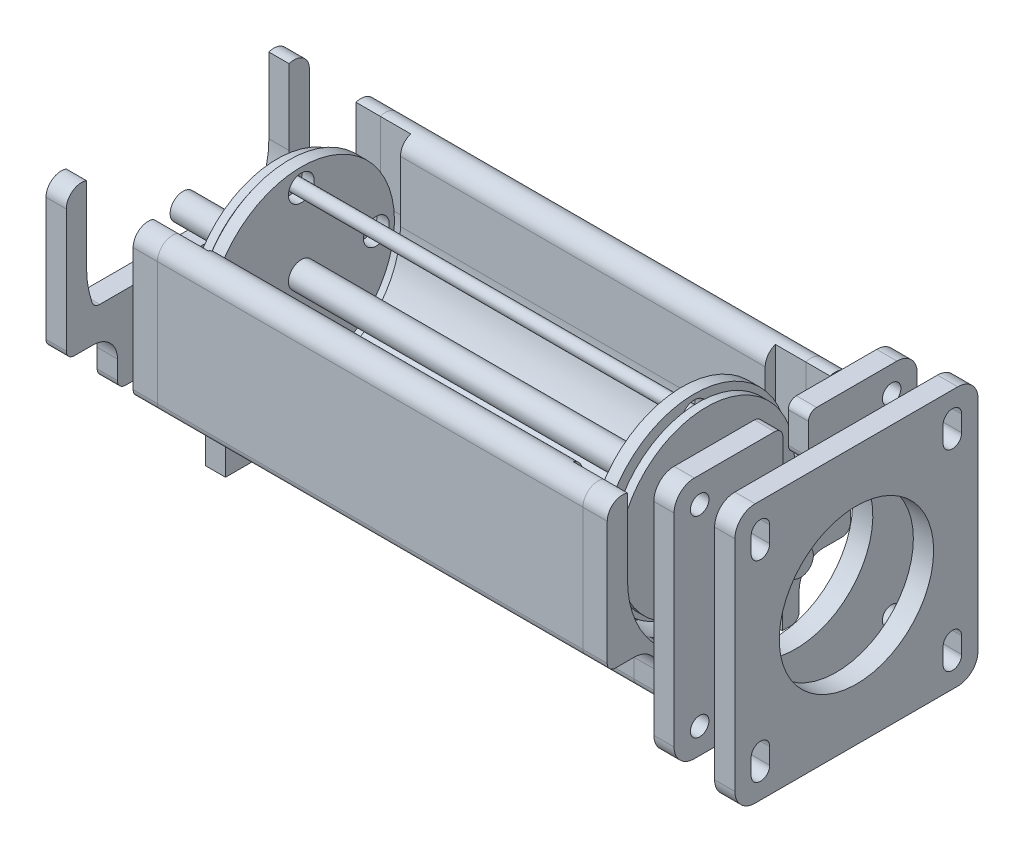
SolidWorks part; units mm, degrees
ref_plane "Front Plane" through (0, 0, 0) normal (0, 0, 1) x (1, 0, 0)
ref_plane "Top Plane" through (0, 0, 0) normal (0, 1, 0) x (1, 0, 0)
ref_plane "Right Plane" through (0, 0, 0) normal (1, 0, 0) x (0, 0, -1)
ref_plane "Plane1" through (-50, 0, 0) normal (1, 0, 0) x (0, 0, -1)
sketch "Sketch2" plane through (-50, 0, 0) normal (1, 0, 0) x (0, 0, -1)
  line L0 (0, 0) -> (0, 1.0694) construction
  circle A0 centre (0, 0) radius 3.175
  circle A1 centre (0, 18.5125) radius 1.5875 construction
  circle A2 centre (0, 18.5125) radius 3.175
  circle A3 centre (0, 0) radius 23
  circle A4 centre (-18.5125, 0) radius 1.5875 construction
  circle A5 centre (-18.5125, 0) radius 3.175
  circle A6 centre (0, -18.5125) radius 1.5875 construction
  circle A7 centre (0, -18.5125) radius 3.175
  circle A8 centre (18.5125, 0) radius 1.5875 construction
  circle A9 centre (18.5125, 0) radius 3.175
  dimension "D1" = 6.35
  dimension "D2" = 3.175
  dimension "D3" = 6.35
  dimension "D4" = 46
extrude "Boss-Extrude2" add sketch "Sketch2" along normal blind 3 separate body
ref_plane "Plane2" through (45, 0, 0) normal (1, 0, 0) x (0, 0, -1)
sketch "Sketch3" plane through (45, 0, 0) normal (1, 0, 0) x (0, 0, -1)
  line L0 (-22.4812, 0) -> (-22.4812, 15)
  line L1 (22.4812, 0) -> (22.4812, 15)
  line L2 (-23.371, -17.371) -> (-30, -17.371)
  line L3 (-30, 15) -> (-30, -17.371)
  line L4 (-17.371, -30) -> (17.371, -30)
  line L5 (-17.371, -23.371) -> (-17.371, -30)
  line L6 (17.371, -23.371) -> (17.371, -30)
  line L7 (23.371, -17.371) -> (30, -17.371)
  line L12 (30, -17.371) -> (30, 15)
  arc A0 (-22.4812, 0) -> (22.4812, 0) centre (0, 0) ccw
  arc A1 (-23.371, -17.371) -> (-17.371, -23.371) centre (-23.371, -23.371) cw
  arc A2 (17.371, -23.371) -> (23.371, -17.371) centre (23.371, -23.371) cw
  arc A3 (-30, 15) -> (-22.4812, 15) centre (-26.2406, 15) cw
  arc A4 (30, 15) -> (22.4812, 15) centre (26.2406, 15) ccw
  dimension "D1" = 6
  dimension "D2" = 6
extrude "Boss-Extrude3" add sketch "Sketch3" against normal blind 90 separate body
fillet "Fillet1" radius 2 4 edges at (0, -30, -17.371) (0, -30, 17.371) (0, -17.371, 30) (0, -17.371, -30)
ref_plane "Plane9" through (-51, 0, 0) normal (1, 0, 0) x (0, 0, -1)
sketch "Sketch16" plane through (-51, 0, 0) normal (1, 0, 0) x (0, 0, -1)
  circle A0 centre (0, 0) radius 21.6875
  circle A1 centre (0, 0) radius 3.175
  dimension "D1" = 6.35
extrude "Boss-Extrude7" add sketch "Sketch16" against normal blind 2 separate body
sketch "Sketch21" plane through (0, 0, 0) normal (1, 0, 0) x (0, 0, -1)
  circle A0 centre (-18.5125, 0) radius 1.5875
  circle A1 centre (0, 18.5125) radius 1.5875
  circle A2 centre (18.5125, 0) radius 1.5875
  circle A3 centre (0, -18.5125) radius 1.5875
  dimension "D1" = 4
extrude "Compression_Rods" add sketch "Sketch21" along normal mid plane 101.6 separate body
mirror "Mirror2" about plane through (0, 0, 0) normal (1, 0, 0) of bodies 102 113
ref_plane "Plane13" through (45, 0, 0) normal (1, 0, 0) x (0, 0, -1)
sketch "Sketch24" plane through (45, 0, 0) normal (1, 0, 0) x (0, 0, -1)
  line L0 (-25, 0) -> (-25, 18.5488)
  line L1 (25, 0) -> (25, 18.5488)
  line L2 (-23.371, -17.371) -> (-30, -17.371)
  line L3 (-30, 15) -> (-30, -17.371)
  line L4 (-17.371, -30) -> (17.371, -30)
  line L5 (-17.371, -23.371) -> (-17.371, -30)
  line L6 (17.371, -23.371) -> (17.371, -30)
  line L7 (23.371, -17.371) -> (30, -17.371)
  line L12 (30, -17.371) -> (30, 15)
  arc A0 (-25, 0) -> (25, 0) centre (0, 0) ccw
  arc A1 (-23.371, -17.371) -> (-17.371, -23.371) centre (-23.371, -23.371) cw
  arc A2 (17.371, -23.371) -> (23.371, -17.371) centre (23.371, -23.371) cw
  arc A3 (-30, 15) -> (-25, 18.5488) centre (-26.2406, 15) cw
  arc A4 (30, 15) -> (25, 18.5488) centre (26.2406, 15) ccw
  dimension "D1" = 6
  dimension "D2" = 6
extrude "Boss-Extrude13" add sketch "Sketch24" along normal blind 7.5 separate body
fillet "Fillet4" radius 2 4 edges at (48.75, -30, 17.371) (48.75, -17.371, 30) (48.75, -30, -17.371) (48.75, -17.371, -30)
ref_plane "Plane12" through (53, 0, 0) normal (1, 0, 0) x (0, 0, -1)
sketch "Sketch25" plane through (53, 0, 0) normal (1, 0, 0) x (0, 0, -1)
  line L0 (-12.7, 0) -> (-12.7, -40)
  line L1 (12.7, 0) -> (12.7, -40)
  line L3 (12.7, -40) -> (-12.7, -40)
  line L4 (-12.7, -40) -> (-12.5635, -39.8925)
  line L5 (-6.35, -12) -> (-6.35, -31)
  line L6 (6.35, -12) -> (6.35, -31)
  line L7 (-2.35, -8) -> (2.35, -8)
  line L9 (-2.35, -35) -> (2.35, -35)
  circle A0 centre (0, 0) radius 6.35
  arc A1 (-12.7, 0) -> (12.7, 0) centre (0, 0) cw
  arc A2 (-6.35, -31) -> (-2.35, -35) centre (-2.35, -31) ccw
  arc A3 (2.35, -35) -> (6.35, -31) centre (2.35, -31) ccw
  arc A4 (6.35, -12) -> (2.35, -8) centre (2.35, -12) ccw
  arc A5 (-6.35, -12) -> (-2.35, -8) centre (-2.35, -12) cw
  dimension "D1" = 4
  dimension "D3" = 12.7
  dimension "D2" = 25.4
  dimension "D4" = 19
extrude "Boss-Extrude14" add sketch "Sketch25" along normal blind 5 separate body
ref_plane "Plane14" through (52.5, 0, 0) normal (1, 0, 0) x (0, 0, -1)
sketch "Sketch26" plane through (52.5, 0, 0) normal (1, 0, 0) x (0, 0, -1)
  line L0 (-25, 0) -> (-25, 18.5488)
  line L1 (0, 0) -> (0, -46.298) construction
  line L2 (-23.371, -17.371) -> (-30, -17.371)
  line L3 (-30, 15) -> (-30, -17.371)
  line L4 (-17.371, -30) -> (-13.2, -30)
  line L5 (-17.371, -23.371) -> (-17.371, -30)
  line L6 (13.2, -30) -> (13.2, -21.2311)
  line L7 (17.371, -23.371) -> (17.371, -30)
  line L8 (17.371, -30) -> (13.2, -30)
  line L10 (30, 15) -> (30, -17.371)
  line L11 (23.371, -17.371) -> (30, -17.371)
  line L12 (25, 0) -> (25, 18.5488)
  line L15 (-13.2, -30) -> (-13.2, -21.2311)
  arc A0 (-25, 0) -> (-13.2, -21.2311) centre (0, 0) ccw
  arc A1 (-23.371, -17.371) -> (-17.371, -23.371) centre (-23.371, -23.371) cw
  arc A2 (30, 15) -> (25, 18.5488) centre (26.2406, 15) ccw
  arc A3 (-30, 15) -> (-25, 18.5488) centre (-26.2406, 15) cw
  arc A4 (23.371, -17.371) -> (17.371, -23.371) centre (23.371, -23.371) ccw
  arc A5 (25, 0) -> (13.2, -21.2311) centre (0, 0) cw
  dimension "D1" = 6
extrude "Boss-Extrude15" add sketch "Sketch26" along normal blind 6 separate body
ref_plane "Plane15" through (70, 0, 0) normal (1, 0, 0) x (0, 0, -1)
sketch "Sketch27" plane through (70, 0, 0) normal (1, 0, 0) x (0, 0, -1)
  line L0 (-5.175, 30) -> (-25, 30)
  line L1 (23.6855, -23.6855) -> (-23.6855, -23.6855) construction
  line L2 (23.6855, -23.6855) -> (23.6855, 23.6855) construction
  line L3 (23.6855, 23.6855) -> (-23.6855, 23.6855) construction
  line L4 (-23.6855, -23.6855) -> (-23.6855, 23.6855) construction
  line L5 (23.6855, -23.6855) -> (-23.6855, 23.6855) construction
  line L6 (23.6855, 23.6855) -> (-23.6855, -23.6855) construction
  line L7 (5.175, 30) -> (25, 30)
  line L8 (-30, 25) -> (-30, -25)
  line L9 (-25, -30) -> (25, -30)
  line L10 (30, 25) -> (30, -25)
  line L11 (-30, 30) -> (30, -30) construction
  line L12 (-30, -30) -> (30, 30) construction
  line L13 (-3.175, 28) -> (-3.175, 20.404)
  line L14 (3.175, 28) -> (3.175, 20.404)
  line L15 (0, 0) -> (0, 18.7836) construction
  circle A0 centre (-23.6855, 23.6855) radius 2.286
  circle A1 centre (23.6855, 23.6855) radius 2.286
  circle A2 centre (-23.6855, -23.6855) radius 2.286
  circle A3 centre (23.6855, -23.6855) radius 2.286
  arc A4 (-19.05, 0) -> (19.05, 0) centre (0, 0) ccw
  arc A5 (-30, -25) -> (-25, -30) centre (-25, -25) ccw
  arc A6 (25, -30) -> (30, -25) centre (25, -25) ccw
  arc A7 (30, 25) -> (25, 30) centre (25, 25) ccw
  arc A8 (-30, 25) -> (-25, 30) centre (-25, 25) cw
  arc A9 (-19.05, 0) -> (-4.6833, 18.4653) centre (0, 0) cw
  arc A10 (19.05, 0) -> (4.6833, 18.4653) centre (0, 0) ccw
  arc A11 (-3.175, 20.404) -> (-4.6833, 18.4653) centre (-5.175, 20.404) cw
  arc A12 (3.175, 20.404) -> (4.6833, 18.4653) centre (5.175, 20.404) ccw
  arc A13 (3.175, 28) -> (5.175, 30) centre (5.175, 28) cw
  arc A14 (-3.175, 28) -> (-5.175, 30) centre (-5.175, 28) ccw
  point P0 (0, 0)
  point P10 (0, 0)
  point P37 (-3.175, 18.7836)
  point P40 (3.175, 18.7836)
  dimension "D3" = 5
  dimension "D1" = 2
  dimension "D2" = 60
  dimension "D5" = 60
extrude "Boss-Extrude17" add sketch "Sketch27" along normal blind 5 separate body
fillet "Fillet7" radius 2 2 edges at (55.5, -30, 17.371) (55.5, -17.371, 30)
fillet "Fillet8" radius 2 2 edges at (55.5, -30, -17.371) (55.5, -17.371, -30)
mirror "Mirror5" about plane through (0, 0, 0) normal (1, 0, 0) of bodies 127
mirror "Mirror6" about plane through (0, 0, 0) normal (1, 0, 0) of bodies 129 130
mirror "Mirror8" about plane through (0, 0, 0) normal (1, 0, 0) of bodies 128
sketch "Sketch28" plane through (0, 0, 0) normal (1, 0, 0) x (0, 0, -1)
  circle A0 centre (0, 0) radius 3.175
extrude "Boss-Extrude19" add sketch "Sketch28" along normal mid plane 152.4
ref_plane "Plane16" through (85, 0, 0) normal (1, 0, 0) x (0, 0, -1)
sketch "Sketch30" plane through (85, 0, 0) normal (1, 0, 0) x (0, 0, -1)
  line L0 (-25.9715, 25.6855) -> (-25.9715, 21.6855)
  line L1 (23.6855, -23.6855) -> (-23.6855, -23.6855) construction
  line L2 (23.6855, -23.6855) -> (23.6855, 23.6855) construction
  line L3 (23.6855, 23.6855) -> (-23.6855, 23.6855) construction
  line L4 (-23.6855, -23.6855) -> (-23.6855, 23.6855) construction
  line L5 (23.6855, -23.6855) -> (-23.6855, 23.6855) construction
  line L6 (23.6855, 23.6855) -> (-23.6855, -23.6855) construction
  line L7 (-25, 32) -> (25, 32)
  line L8 (-30, 27) -> (-30, -27)
  line L9 (-25, -32) -> (25, -32)
  line L10 (30, 27) -> (30, -27)
  line L11 (-30, 32) -> (30, -32) construction
  line L12 (-30, -32) -> (30, 32) construction
  line L13 (-21.3995, 25.6855) -> (-21.3995, 21.6855)
  line L14 (21.3995, 25.6855) -> (21.3995, 21.6855)
  line L16 (25.9715, 25.6855) -> (25.9715, 21.6855)
  line L18 (25.9715, -25.6855) -> (25.9715, -21.6855)
  line L19 (21.3995, -25.6855) -> (21.3995, -21.6855)
  line L20 (-21.3995, -25.6855) -> (-21.3995, -21.6855)
  line L21 (-25.9715, -25.6855) -> (-25.9715, -21.6855)
  arc A0 (25.9715, 25.6855) -> (21.3995, 25.6855) centre (23.6855, 25.6855) ccw
  arc A1 (25.9715, 21.6855) -> (21.3995, 21.6855) centre (23.6855, 21.6855) cw
  arc A2 (25.9715, -21.6855) -> (21.3995, -21.6855) centre (23.6855, -21.6855) ccw
  arc A3 (25.9715, -25.6855) -> (21.3995, -25.6855) centre (23.6855, -25.6855) cw
  arc A4 (-25.9715, 25.6855) -> (-21.3995, 25.6855) centre (-23.6855, 25.6855) cw
  arc A5 (-25, 32) -> (-30, 27) centre (-25, 27) ccw
  arc A6 (-30, -27) -> (-25, -32) centre (-25, -27) ccw
  arc A7 (25, -32) -> (30, -27) centre (25, -27) ccw
  arc A8 (25, 32) -> (30, 27) centre (25, 27) cw
  circle A9 centre (0, 0) radius 19.05
  arc A10 (-25.9715, 21.6855) -> (-21.3995, 21.6855) centre (-23.6855, 21.6855) ccw
  arc A11 (-25.9715, -21.6855) -> (-21.3995, -21.6855) centre (-23.6855, -21.6855) cw
  arc A12 (-25.9715, -25.6855) -> (-21.3995, -25.6855) centre (-23.6855, -25.6855) ccw
  point P0 (0, 0)
  point P10 (0, 0)
  dimension "D3" = 5
  dimension "D1" = 5
  dimension "D2" = 60
  dimension "D5" = 64
extrude "Boss-Extrude21" add sketch "Sketch30" along normal blind 5 separate body
ref_plane "Plane17" through (-75, 0, 0) normal (1, 0, 0) x (0, 0, -1)
sketch "Sketch34" plane through (-75, 0, 0) normal (1, 0, 0) x (0, 0, -1)
  line L0 (-25, 0) -> (-25, 18.5488)
  line L1 (25, 0) -> (25, 18.5488)
  line L2 (-23.371, -17.371) -> (-28, -17.371)
  line L3 (-30, 15) -> (-30, -15.371)
  line L4 (-15.371, -30) -> (15.371, -30)
  line L5 (-17.371, -23.371) -> (-17.371, -28)
  line L6 (17.371, -23.371) -> (17.371, -28)
  line L7 (23.371, -17.371) -> (28, -17.371)
  line L8 (21.7342, -9.525) -> (-21.7342, -9.525)
  line L9 (0, 0) -> (0, -13.7519) construction
  line L12 (30, -15.371) -> (30, 15)
  arc A0 (23.6241, -8.1793) -> (25, 0) centre (0, 0) ccw
  arc A1 (-23.371, -17.371) -> (-17.371, -23.371) centre (-23.371, -23.371) cw
  arc A2 (17.371, -23.371) -> (23.371, -17.371) centre (23.371, -23.371) cw
  arc A3 (-30, 15) -> (-25, 18.5488) centre (-26.2406, 15) cw
  arc A4 (30, 15) -> (25, 18.5488) centre (26.2406, 15) ccw
  arc A5 (-23.6241, -8.1793) -> (-21.7342, -9.525) centre (-21.7342, -7.525) ccw
  arc A6 (-23.6241, -8.1793) -> (-25, 0) centre (0, 0) cw
  arc A7 (-28, -17.371) -> (-30, -15.371) centre (-28, -15.371) cw
  arc A8 (23.6241, -8.1793) -> (21.7342, -9.525) centre (21.7342, -7.525) cw
  arc A9 (-17.371, -28) -> (-15.371, -30) centre (-15.371, -28) ccw
  arc A10 (17.371, -28) -> (15.371, -30) centre (15.371, -28) cw
  arc A11 (28, -17.371) -> (30, -15.371) centre (28, -15.371) ccw
  dimension "D1" = 6
  dimension "D2" = 6
  dimension "D3" = 2
  dimension "D4" = 2
extrude "Boss-Extrude22" add sketch "Sketch34" against normal blind 5 separate body
